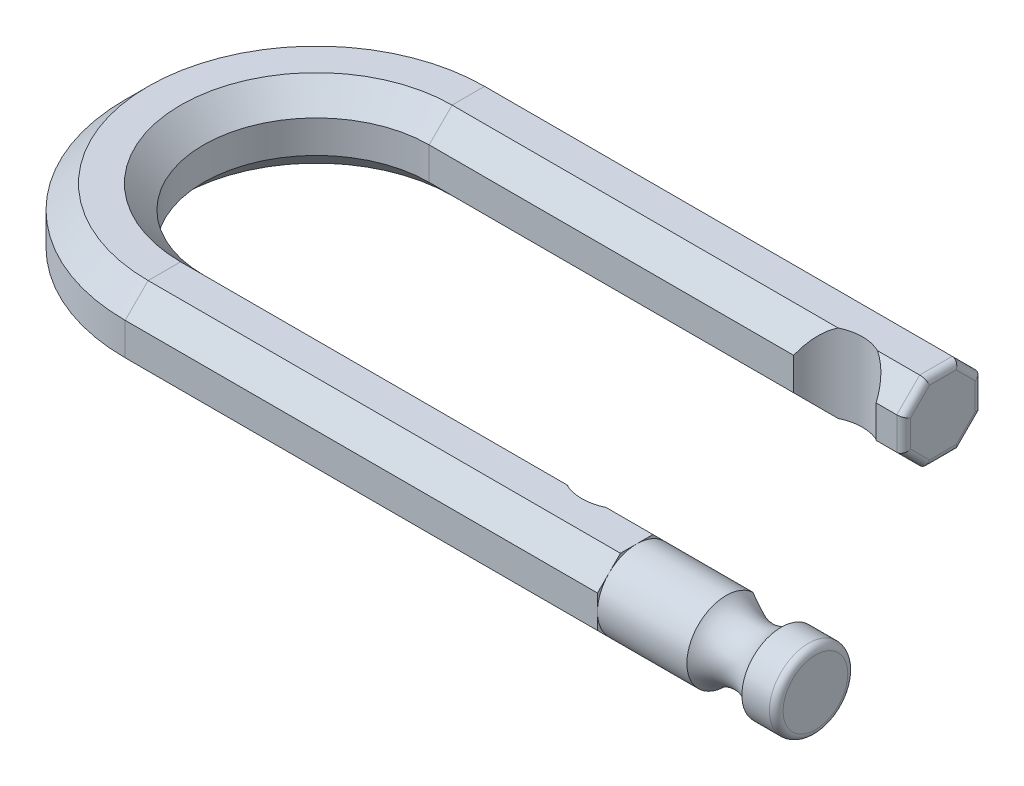
SolidWorks part; units mm, degrees
ref_plane "Front" through (0, 0, 0) normal (0, 0, 1) x (1, 0, 0)
ref_plane "Top" through (0, 0, 0) normal (0, 1, 0) x (1, 0, 0)
ref_plane "Right" through (0, 0, 0) normal (1, 0, 0) x (0, 0, -1)
sketch "Sketch1" plane through (0, 0, 0) normal (0, 1, 0) x (1, 0, 0)
  line L0 (0, 0) -> (-60.1218, 0)
  line L1 (-60.1218, 35.306) -> (-16.3068, 35.306)
  arc A0 (-60.1218, 0) -> (-60.1218, 35.306) centre (-60.1218, 17.653) cw
  point P5 (-77.7748, 17.653)
  dimension "D3" = 35.306
  dimension "D1" = 61.468
  dimension "D2" = 77.7748
sketch "Sketch2" plane through (0, 0, 0) normal (1, 0, 0) x (0, 0, -1)
  line L1 (7.239, 1.4992) -> (5.1187, 3.6195)
  line L2 (5.1187, 3.6195) -> (2.1203, 3.6195)
  line L3 (2.1203, 3.6195) -> (0, 1.4992)
  line L4 (0, 1.4992) -> (0, -1.4992)
  line L5 (0, -1.4992) -> (2.1203, -3.6195)
  line L6 (2.1203, -3.6195) -> (5.1187, -3.6195)
  line L7 (5.1187, -3.6195) -> (7.239, -1.4992)
  line L8 (7.239, -1.4992) -> (7.239, 1.4992)
  circle A0 centre (3.6195, 0) radius 3.6195 construction
  point P1 (0, 0)
  dimension "D1" = 7.239
sweep "Sweep1" add profiles "Sketch2" path "Sketch1"
sketch "Sketch3" plane through (0, 0, 0) normal (1, 0, 0) x (0, 0, -1)
  line L0 (2.1203, 3.6195) -> (0, 1.4992) construction
  circle A0 centre (3.6195, 0) radius 3.6195
  circle A1 centre (3.6195, 0) radius 3.9177
extrude "Cut-Extrude1" cut sketch "Sketch3" against normal blind 16.51
sketch "Sketch5" plane through (0, 0, 0) normal (0, 1, 0) x (1, 0, 0)
  line L0 (0, 7.239) -> (-3.175, 7.239) construction
  line L1 (0, 7.239) -> (-16.51, 7.239) construction
  line L2 (-8.255, 7.239) -> (-3.175, 7.239)
  line L3 (0, 3.6195) -> (-16.51, 3.6195) construction
  line L4 (0, 0) -> (0, 7.239) construction
  arc A0 (-3.175, 7.239) -> (-8.255, 7.239) centre (-5.715, 9.4897) cw
  point P12 (-5.715, 6.096)
  point P13 (0, 0)
  dimension "D1" = 4.953
  dimension "D2" = 3.175
  dimension "D3" = 5.08
revolve "Cut-Revolve1" cut sketch "Sketch5" angle 360 about L3
sketch "Sketch6" plane through (0, 0, 0) normal (0, 1, 0) x (1, 0, 0)
  line L0 (-18.8468, 28.067) -> (-26.4668, 28.067)
  line L1 (-60.1218, 28.067) -> (-16.3068, 28.067) construction
  line L2 (-18.8468, 7.239) -> (-26.4668, 7.239)
  line L3 (-16.51, 7.239) -> (-60.1218, 7.239) construction
  line L4 (-60.1218, 35.306) -> (-16.3068, 35.306) construction
  line L6 (-16.51, 0) -> (-60.1218, 0) construction
  line L7 (-16.3068, 28.067) -> (-16.3068, 30.1873) construction
  arc A1 (-26.4668, 28.067) -> (-18.8468, 28.067) centre (-22.6568, 26.4795) cw
  arc A2 (-26.4668, 7.239) -> (-18.8468, 7.239) centre (-22.6568, 8.8265) ccw
  point P12 (-22.6568, 30.607)
  point P13 (-22.6568, 4.699)
  point P16 (0, 0)
  point P17 (0, 0)
  point P18 (0, 0)
  dimension "D1" = 4.699
  dimension "D4" = 7.62
  dimension "D2" = 4.699
  dimension "D3" = 2.54
extrude "Cut-Extrude2" cut sketch "Sketch6" against normal through all both and the other way through all
sketch "Sketch7" plane through (0, 0, 0) normal (0, 1, 0) x (1, 0, 0)
  line L0 (-5.715, 6.096) -> (-19.5615, 6.096)
  line L1 (-18.8468, 7.239) -> (-8.255, 7.239)
  line L3 (-16.51, 0) -> (-8.255, 0) construction
  arc A0 (-8.255, 7.239) -> (-3.175, 7.239) centre (-5.715, 9.4897) ccw construction
  arc A1 (-20.8433, 5.1187) -> (-18.8468, 7.239) centre (-22.6568, 8.8265) ccw construction
  arc A2 (-19.5615, 6.096) -> (-18.8468, 7.239) centre (-22.6568, 8.8265) ccw
  arc A3 (-8.255, 7.239) -> (-5.715, 6.096) centre (-5.715, 9.4897) ccw
  point P14 (0, 0)
  dimension "D1" = 6.096
extrude "Cut-Extrude3" cut sketch "Sketch7" against normal through all both and the other way through all
fillet "Fillet1" radius 0.635 9 edges at (0, 0, -7.239) (-16.3068, 2.5594, -29.1271) (-16.3068, 3.6195, -31.6865) (-16.3068, 2.5594, -34.2459) (-16.3068, 0, -35.306) (-16.3068, -2.5594, -34.2459) (-16.3068, -3.6195, -31.6865) (-16.3068, -2.5594, -29.1271) (-16.3068, 0, -28.067)
